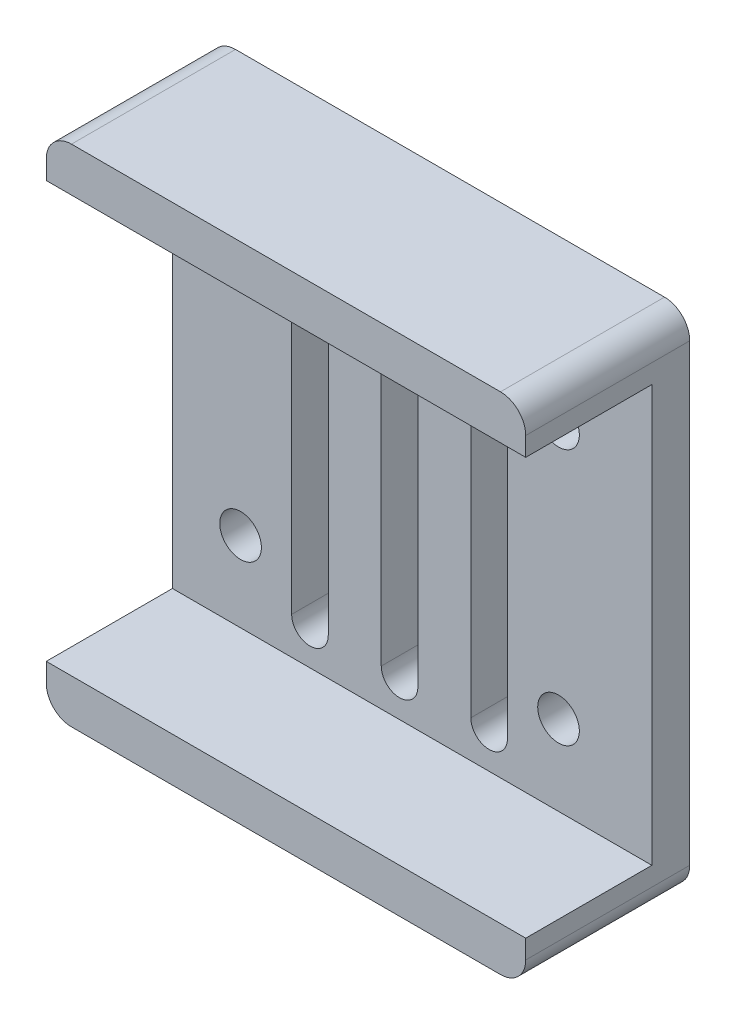
SolidWorks part; units mm, degrees
ref_plane "Front Plane" through (0, 0, 0) normal (0, 0, 1) x (1, 0, 0)
ref_plane "Top Plane" through (0, 0, 0) normal (0, 1, 0) x (1, 0, 0)
ref_plane "Right Plane" through (0, 0, 0) normal (1, 0, 0) x (0, 0, -1)
sketch "Sketch1" plane through (0, 0, 0) normal (0, 0, 1) x (1, 0, 0)
  line L0 (0, 0) -> (0, 20) construction
  line L5 (12.6, -10.16) -> (-12.6, 10.16) construction
  line L6 (12.6, 10.16) -> (-12.6, -10.16) construction
  line L7 (0, 0) -> (0, -20) construction
  line L8 (12.6, -10.16) -> (12.6, 10.16) construction
  line L9 (-12.6, -10.16) -> (-12.6, 10.16) construction
  line L10 (-12.6, 10.16) -> (12.6, 10.16) construction
  line L11 (-12.6, -10.16) -> (12.6, -10.16) construction
  line L12 (0, 20) -> (-16, 20)
  line L13 (0, -20) -> (-16, -20)
  line L14 (-18, 18) -> (-18, -18)
  line L15 (0, 20) -> (18, 20)
  line L16 (0, -20) -> (18, -20)
  line L17 (20, -18) -> (20, 18)
  circle A0 centre (-12.6, 10.16) radius 1.65
  circle A1 centre (12.6, 10.16) radius 1.65
  circle A2 centre (12.6, -10.16) radius 1.65
  circle A3 centre (-12.6, -10.16) radius 1.65
  arc A4 (18, -20) -> (20, -18) centre (18, -18) ccw
  arc A5 (20, 18) -> (18, 20) centre (18, 18) ccw
  arc A6 (-16, -20) -> (-18, -18) centre (-16, -18) cw
  arc A7 (-18, 18) -> (-16, 20) centre (-16, 18) cw
  point P0 (0, 0)
  point P21 (20, 20)
  point P24 (-18, -20)
  point P27 (-18, 20)
  dimension "D3" = 3.3
  dimension "D4" = 3.3
  dimension "D5" = 3.3
  dimension "D6" = 3.3
  dimension "D12" = 2
  dimension "D1" = 25.2
  dimension "D2" = 20.32
  dimension "D7" = 20
  dimension "D8" = 20
  dimension "D9" = 18
  dimension "D10" = 18
  dimension "D11" = 20
extrude "Boss-Extrude1" add sketch "Sketch1" along normal blind 13
ref_plane "Plane1" through (0, 0, 13) normal (0, 0, 1) x (1, 0, 0)
sketch "Sketch2" plane through (0, 0, 13) normal (0, 0, 1) x (1, 0, 0)
  line L1 (5.65, -13.55) -> (5.65, 13.55)
  line L7 (1.45, -13.55) -> (1.45, 13.55)
  line L16 (-1.45, -13.55) -> (-1.45, 13.55)
  line L17 (8.55, -13.55) -> (8.55, 13.55)
  line L18 (-8.55, -13.55) -> (-8.55, 13.55)
  line L19 (-5.65, -13.55) -> (-5.65, 13.55)
  arc A11 (1.45, 13.55) -> (-1.45, 13.55) centre (0, 13.55) ccw
  arc A12 (-1.45, -13.55) -> (1.45, -13.55) centre (0, -13.55) ccw
  arc A13 (8.55, 13.55) -> (5.65, 13.55) centre (7.1, 13.55) ccw
  arc A14 (5.65, -13.55) -> (8.55, -13.55) centre (7.1, -13.55) ccw
  arc A15 (-5.65, 13.55) -> (-8.55, 13.55) centre (-7.1, 13.55) ccw
  arc A16 (-8.55, -13.55) -> (-5.65, -13.55) centre (-7.1, -13.55) ccw
  point P0 (0, 0)
  dimension "D1" = 2.9
  dimension "D2" = 27.1
  dimension "D3" = 2
  dimension "D4" = 2
extrude "Cut-Extrude1" cut sketch "Sketch2" against normal through all
ref_plane "Plane2" through (0, 0, 13) normal (0, 0, 1) x (1, 0, 0)
sketch "Sketch3" plane through (0, 0, 13) normal (0, 0, 1) x (1, 0, 0)
  line L1 (26.3592, -16.5) -> (-26.3592, -16.5)
  line L2 (26.3592, -16.5) -> (26.3592, 16.5)
  line L3 (26.3592, 16.5) -> (-26.3592, 16.5)
  line L4 (-26.3592, -16.5) -> (-26.3592, 16.5)
  line L5 (26.3592, -16.5) -> (-26.3592, 16.5) construction
  line L6 (26.3592, 16.5) -> (-26.3592, -16.5) construction
  point P0 (0, 0)
  dimension "D1" = 33
extrude "Cut-Extrude2" cut sketch "Sketch3" against normal blind 10
